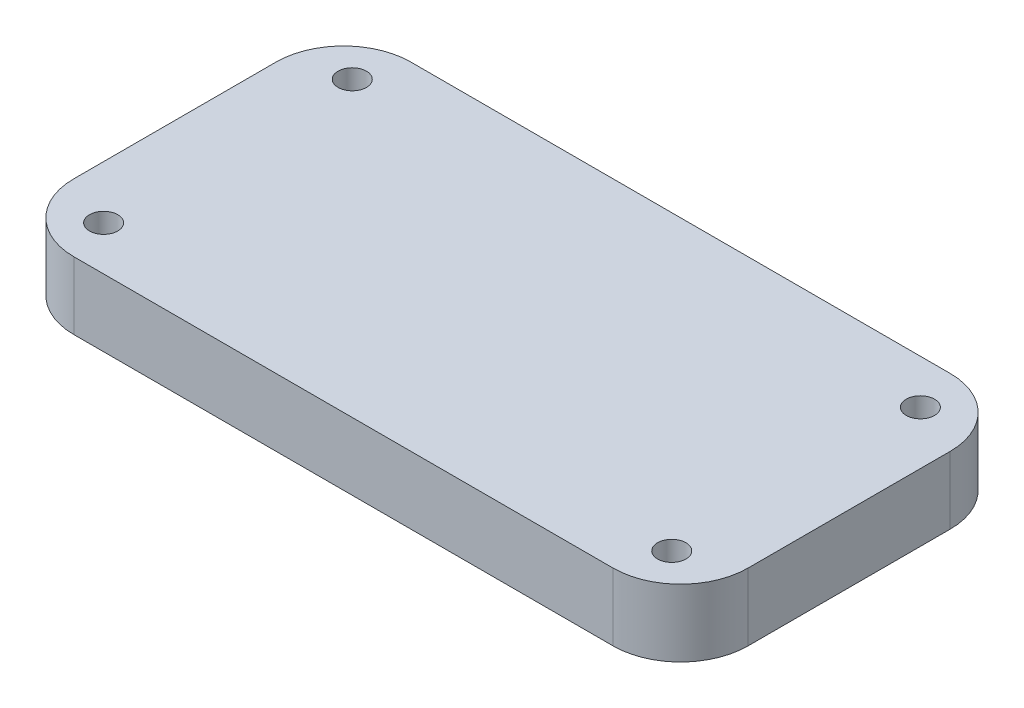
SolidWorks part; units mm, degrees
ref_plane "Front Plane" through (0, 0, 0) normal (0, 0, 1) x (1, 0, 0)
ref_plane "Top Plane" through (0, 0, 0) normal (0, 1, 0) x (1, 0, 0)
ref_plane "Right Plane" through (0, 0, 0) normal (1, 0, 0) x (0, 0, -1)
sketch "Sketch1" plane through (0, 0, 0) normal (0, 1, 0) x (1, 0, 0)
  line L1 (-50, 25) -> (50, 25)
  line L2 (-50, 25) -> (-50, -25)
  line L3 (-50, -25) -> (50, -25)
  line L4 (50, 25) -> (50, -25)
  point P4 (0, 25)
  point P6 (-50, 0)
  dimension "D1" = 100
  dimension "D2" = 50
extrude "Boss-Extrude1" add sketch "Sketch1" along normal blind 10
fillet "Fillet1" radius 10 4 edges at (-50, 5, -25) (50, 5, -25) (50, 5, 25) (-50, 5, 25)
sketch "Sketch2" plane through (0, 10, 0) normal (0, 1, 0) x (1, 0, 0)
  line L1 (-42.1324, 18.4389) -> (42.1324, 18.4389) construction
  line L2 (-42.1324, 18.4389) -> (-42.1324, -18.4389) construction
  line L3 (-42.1324, -18.4389) -> (42.1324, -18.4389) construction
  line L4 (42.1324, 18.4389) -> (42.1324, -18.4389) construction
  circle A0 centre (-42.1324, 18.4389) radius 2.1
  circle A1 centre (42.1324, 18.4389) radius 2.1
  circle A2 centre (42.1324, -18.4389) radius 2.1
  circle A3 centre (-42.1324, -18.4389) radius 2.1
  point P4 (0, 18.4389)
  point P6 (-42.1324, 0)
  dimension "D1" = 4.2
extrude "Cut-Extrude1" cut sketch "Sketch2" against normal blind 10
